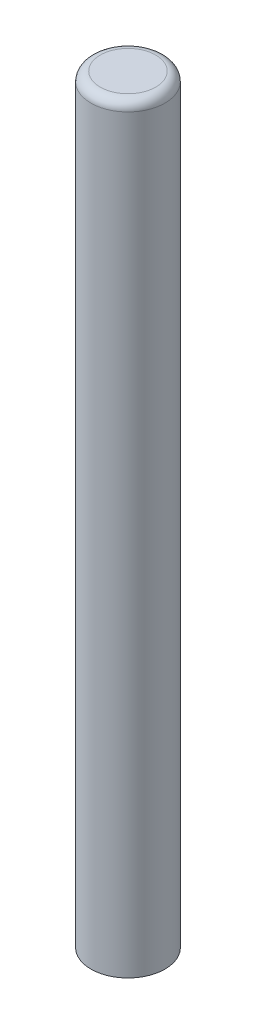
SolidWorks part; units mm, degrees
material "Plain Carbon Steel"
ref_plane "Front Plane" through (0, 0, 0) normal (0, 0, 1) x (1, 0, 0)
ref_plane "Top Plane" through (0, 0, 0) normal (0, 1, 0) x (1, 0, 0)
ref_plane "Right Plane" through (0, 0, 0) normal (1, 0, 0) x (0, 0, -1)
sketch "Sketch1" plane through (0, 0, 0) normal (0, 1, 0) x (1, 0, 0)
  circle A0 centre (0, 0) radius 1
  dimension "D1" = 2
extrude "Boss-Extrude1" add sketch "Sketch1" along normal blind 20.5
fillet "Fillet1" radius 0.25 1 edges at (0, 20.5, 1)
